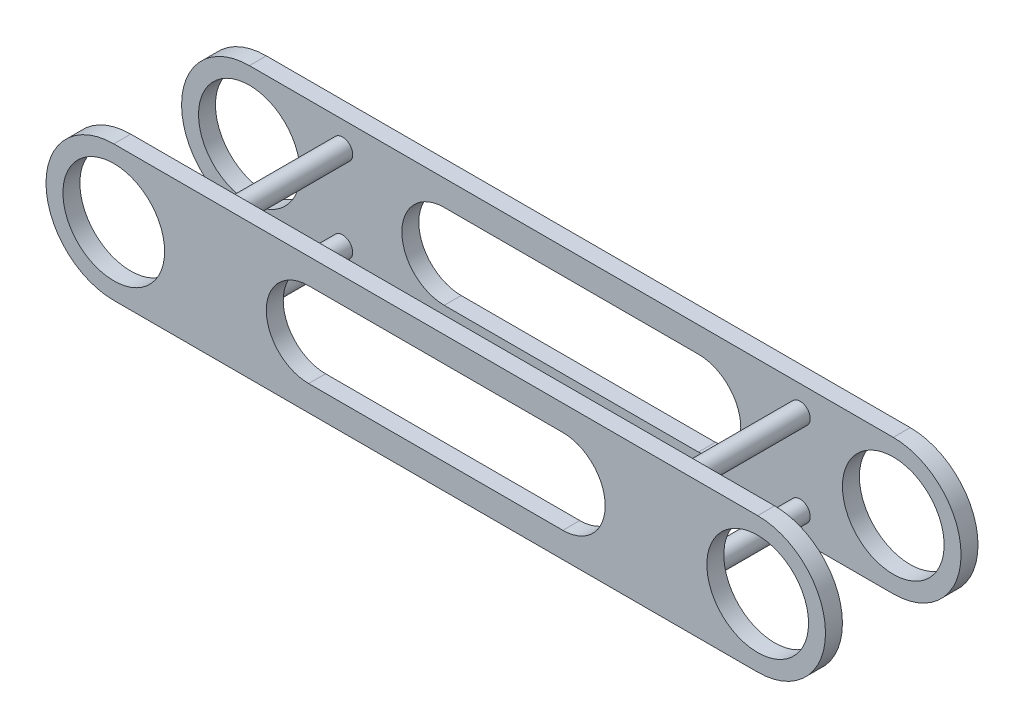
SolidWorks part; units mm, degrees
ref_plane "Front Plane" through (0, 0, 0) normal (0, 0, 1) x (1, 0, 0)
ref_plane "Top Plane" through (0, 0, 0) normal (0, 1, 0) x (1, 0, 0)
ref_plane "Right Plane" through (0, 0, 0) normal (1, 0, 0) x (0, 0, -1)
sketch "Sketch1" plane through (0, 0, 0) normal (0, 0, 1) x (1, 0, 0)
  circle A0 centre (0, 0) radius 30
  dimension "D1" = 60
extrude "Boss-Extrude1" add sketch "Sketch1" along normal mid plane 105
ref_plane "Plane1" through (0, 0, 45) normal (0, 0, 1) x (1, 0, 0)
sketch "Sketch2" plane through (0, 0, 45) normal (0, 0, 1) x (1, 0, 0)
  line L0 (0, 40) -> (0, -40) construction
  line L1 (0, 40) -> (380, 40)
  line L2 (0, 0) -> (380, 0) construction
  line L3 (380, 40) -> (380, -40) construction
  line L4 (0, -40) -> (380, -40)
  arc A0 (0, 40) -> (0, -40) centre (0, 0) ccw
  arc A1 (380, -40) -> (380, 40) centre (380, 0) ccw
  point P6 (0, 0)
  point P10 (380, 0)
  dimension "D1" = 40
  dimension "D2" = 380
extrude "Boss-Extrude2" add sketch "Sketch2" against normal blind 10
sketch "Sketch4" plane through (0, 0, 45) normal (0, 0, 1) x (1, 0, 0)
  line L0 (0, 0) -> (380, 0) construction
  line L1 (265, 0) -> (115, 0) construction
  line L2 (265, -25) -> (115, -25)
  line L3 (265, 25) -> (115, 25)
  arc A0 (265, -25) -> (265, 25) centre (265, 0) ccw
  arc A1 (115, 25) -> (115, -25) centre (115, 0) ccw
  point P6 (190, 0)
  dimension "D2" = 25
  dimension "D1" = 150
extrude "Cut-Extrude1" cut sketch "Sketch4" against normal up to next
sketch "Sketch5" plane through (0, 0, 0) normal (0, 0, 1) x (1, 0, 0)
  circle A0 centre (380, 0) radius 30
  dimension "D1" = 60
extrude "Boss-Extrude3" add sketch "Sketch5" along normal mid plane 105
mirror "Mirror1" about plane through (0, 0, 0) normal (0, 0, 1) of "Cut-Extrude1", "Boss-Extrude2"
sketch "Sketch6" plane through (0, 0, 45) normal (0, 0, 1) x (1, 0, 0)
  line L0 (0, 0) -> (380, 0) construction
  line L2 (55, 25) -> (325, 25) construction
  line L3 (55, 25) -> (55, -25) construction
  line L4 (55, -25) -> (325, -25) construction
  line L5 (325, 25) -> (325, -25) construction
  line L6 (55, 25) -> (325, -25) construction
  line L7 (55, -25) -> (325, 25) construction
  circle A0 centre (55, 25) radius 6
  circle A1 centre (55, -25) radius 6
  circle A2 centre (325, -25) radius 6
  circle A3 centre (325, 25) radius 6
  point P4 (190, 0)
  dimension "D3" = 12
  dimension "D1" = 50
  dimension "D2" = 270
extrude "Boss-Extrude4" add sketch "Sketch6" against normal up to surface (80 mm away) up to face at (190, 0, -35)
sketch "Sketch7" plane through (0, 0, 52.5) normal (0, 0, 1) x (1, 0, 0)
  circle A0 centre (380, 0) radius 30 construction
  circle A1 centre (0, 0) radius 30 construction
  circle A2 centre (380, 0) radius 30
  circle A3 centre (0, 0) radius 30
extrude "Cut-Extrude2" cut sketch "Sketch7" against normal through all
